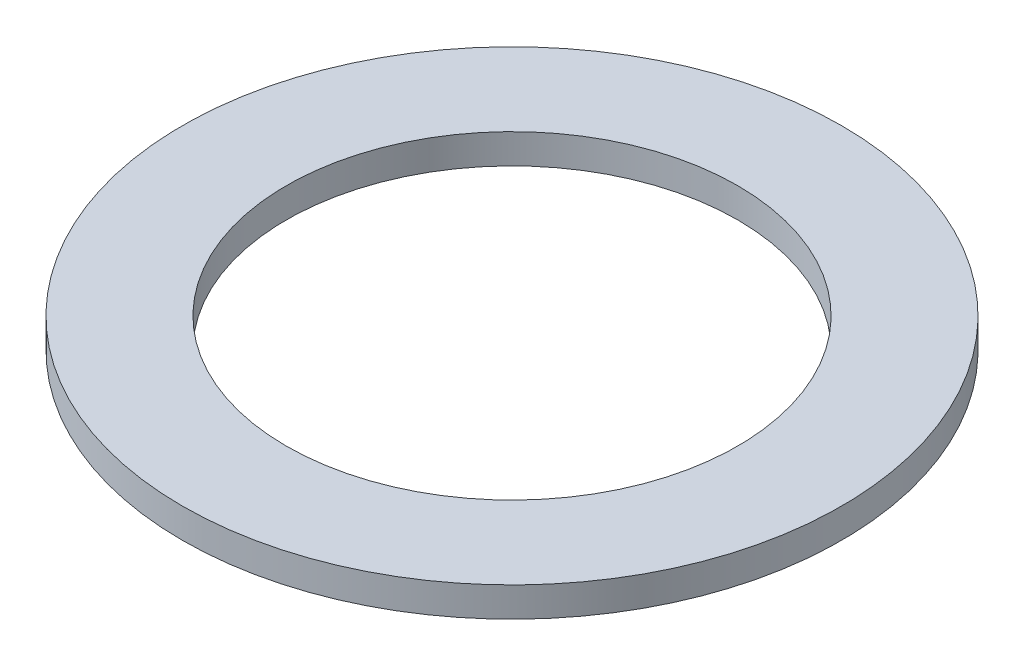
SolidWorks part; units mm, degrees
ref_plane "Front Plane" through (0, 0, 0) normal (0, 0, 1) x (1, 0, 0)
ref_plane "Top Plane" through (0, 0, 0) normal (0, 1, 0) x (1, 0, 0)
ref_plane "Right Plane" through (0, 0, 0) normal (1, 0, 0) x (0, 0, -1)
sketch "Sketch1" plane through (0, 0, 0) normal (0, 0, 1) x (1, 0, 0)
  line L0 (0, 0) -> (-11.1, 0) construction
  line L1 (-11.1, 0) -> (-7.6, 0)
  line L2 (-7.6, 0) -> (-7.6, 1)
  line L3 (-7.6, 1) -> (-11.1, 1)
  line L4 (-11.1, 1) -> (-11.1, 0)
  line L5 (0, 0) -> (0, 3.2037) construction
  dimension "D1" = 11.1
  dimension "D2" = 1
  dimension "D3" = 3.5
revolve "Revolve1" add sketch "Sketch1" angle 360 about L5
